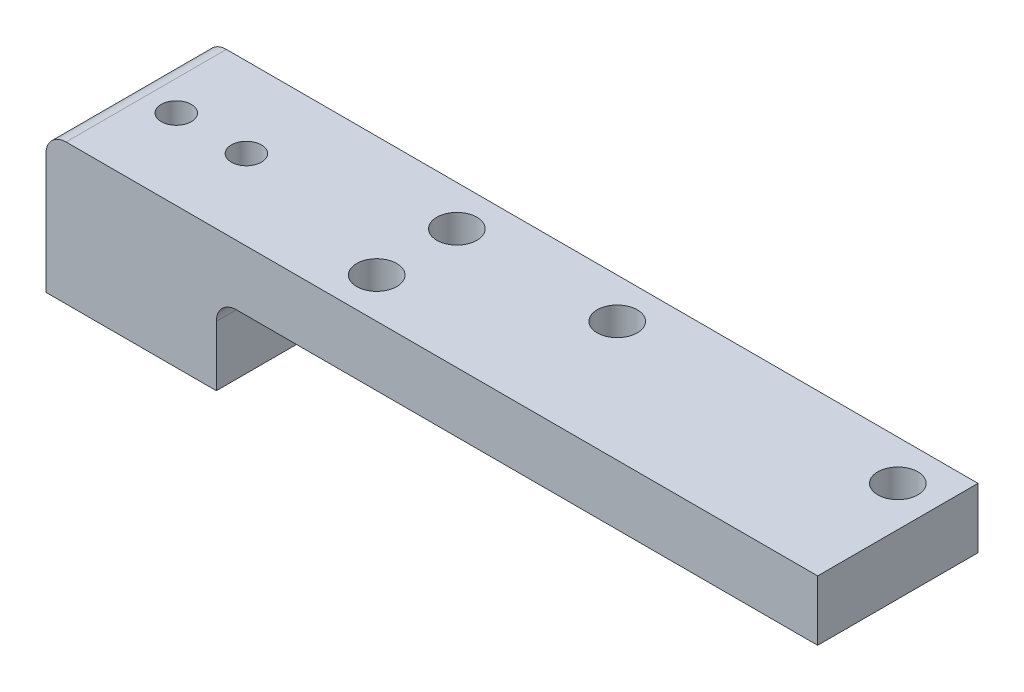
SolidWorks part; units mm, degrees
material "Stainless Steel (ferritic)"
ref_plane "Front Plane" through (0, 0, 0) normal (0, 0, 1) x (1, 0, 0)
ref_plane "Top Plane" through (0, 0, 0) normal (0, 1, 0) x (1, 0, 0)
ref_plane "Right Plane" through (0, 0, 0) normal (1, 0, 0) x (0, 0, -1)
sketch "Sketch1" plane through (0, 0, 0) normal (0, 1, 0) x (1, 0, 0)
  line L0 (-8.5, 0) -> (8.5, 0) construction
  line L1 (-8.5, 8) -> (8.5, 8)
  line L2 (-8.5, 8) -> (-8.5, -8)
  line L3 (-8.5, -8) -> (8.5, -8)
  line L4 (8.5, 8) -> (8.5, -8)
  line L5 (-8.5, 8) -> (8.5, -8) construction
  line L6 (-8.5, -8) -> (8.5, 8) construction
  circle A0 centre (-3.5, 0) radius 1.5
  circle A1 centre (3.5, 0) radius 1.5
  point P0 (0, 0)
  dimension "D3" = 3
  dimension "D4" = 3
  dimension "D1" = 17
  dimension "D2" = 16
  dimension "D5" = 7
  dimension "D6" = 5
extrude "Boss-Extrude1" add sketch "Sketch1" along normal blind 14
sketch "Sketch3" plane through (8.5, 0, 0) normal (1, 0, 0) x (0, 0, -1)
  line L1 (-8, 14) -> (8, 14)
  line L2 (-8, 14) -> (-8, 8)
  line L3 (-8, 8) -> (8, 8)
  line L4 (8, 14) -> (8, 8)
  dimension "D1" = 6
extrude "Boss-Extrude2" add sketch "Sketch3" along normal blind 60
sketch "Sketch4" plane through (0, 14, 0) normal (0, 1, 0) x (1, 0, 0)
  line L0 (36.5, 4) -> (64.5, 4) construction
  line L1 (64.5, 4) -> (68.5, 4) construction
  line L2 (68.5, 8) -> (68.5, -8) construction
  line L3 (32.5, 8) -> (32.5, -8) construction
  line L4 (68.5, 8) -> (-8.5, 8) construction
  line L5 (-8.5, -8) -> (68.5, -8) construction
  line L6 (32.5, 4) -> (36.5, 4) construction
  line L7 (36.5, 8) -> (36.5, -8) construction
  line L8 (64.5, 8) -> (64.5, -8) construction
  line L9 (20.5, 8) -> (20.5, 4) construction
  line L10 (20.5, 4) -> (20.5, -4) construction
  line L11 (20.5, -4) -> (20.5, -8) construction
  line L12 (8.5, 8) -> (8.5, -8) construction
  line L13 (20.5, 4) -> (8.5, 4) construction
  line L14 (20.5, 4) -> (32.5, 4) construction
  circle A0 centre (36.5, 4) radius 2
  circle A1 centre (64.5, 4) radius 2
  circle A2 centre (20.5, 4) radius 2
  circle A3 centre (20.5, -4) radius 2
  circle A4 centre (20.5, 4) radius 3.75 construction
  circle A5 centre (20.5, -4) radius 3.75 construction
  dimension "D1" = 4
  dimension "D2" = 4
  dimension "D6" = 4
  dimension "D7" = 4
  dimension "D8" = 7.5
  dimension "D3" = 28
  dimension "D4" = 36
  dimension "D5" = 4
  dimension "D9" = 17
  dimension "D10" = 8
extrude "Cut-Extrude1" cut sketch "Sketch4" against normal through all
fillet "Fillet1" radius 2 1 edges at (8.5, 8, 0)
fillet "Fillet2" radius 2 1 edges at (-8.5, 14, 0)
